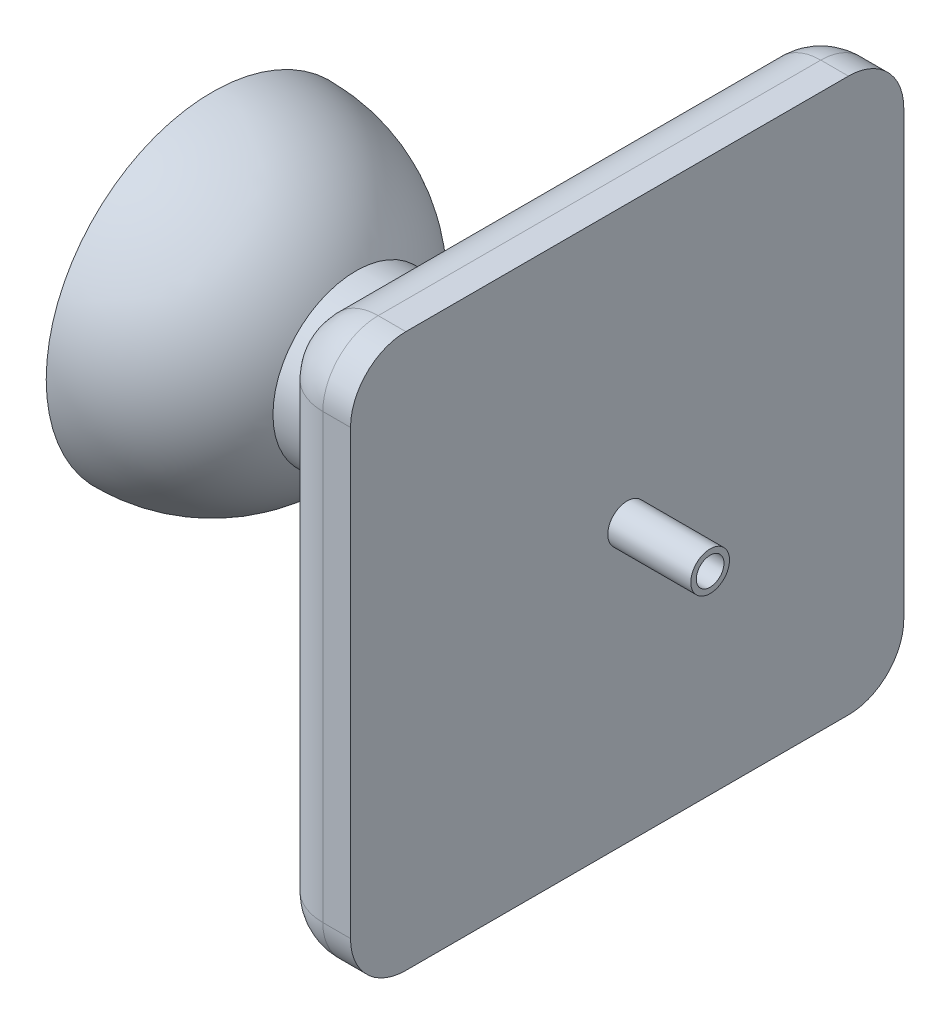
SolidWorks part; units mm, degrees
ref_plane "Alzado" through (0, 0, 0) normal (0, 0, 1) x (1, 0, 0)
ref_plane "Planta" through (0, 0, 0) normal (0, 1, 0) x (1, 0, 0)
ref_plane "Vista lateral" through (0, 0, 0) normal (1, 0, 0) x (0, 0, -1)
sketch "Croquis2" plane through (0, 0, 0) normal (0, 0, 1) x (1, 0, 0)
  line L2 (0, 0) -> (25, 0) construction
  arc A0 (25, 0) -> (0, 25) centre (0, 0) ccw
  dimension "D1" = 50
revolve "Revolución-Lámina1" add sketch "Croquis2" angle 360 about L2
sketch "Croquis3" plane through (0, 0, 0) normal (-1, 0, 0) x (0, 0, 1)
  circle A0 centre (0, 0) radius 15
  dimension "D1" = 30
extrude "Saliente-Extruir1" add sketch "Croquis3" against normal blind 20 and the other way up to surface from offset 40 offset against normal yes
sketch "Croquis4" plane through (60, 0, 0) normal (1, 0, 0) x (0, 0, -1)
  line L1 (-50, -50) -> (50, -50)
  line L2 (-50, -50) -> (-50, 50)
  line L3 (-50, 50) -> (50, 50)
  line L4 (50, -50) -> (50, 50)
  line L5 (-50, -50) -> (50, 50) construction
  line L6 (-50, 50) -> (50, -50) construction
  point P0 (0, 0)
  dimension "D1" = 100
  dimension "D2" = 100
extrude "Saliente-Extruir2" add sketch "Croquis4" along normal blind 15
fillet "Redondeo1" radius 10 4 edges at (67.5, -50, -50) (67.5, -50, 50) (67.5, 50, 50) (67.5, 50, -50)
fillet "Redondeo2" radius 10 8 edges at (60, -47.0711, -47.0711) (60, -50, 0) (60, -47.0711, 47.0711) (60, 0, 50) (60, 47.0711, 47.0711) (60, 50, 0) (60, 47.0711, -47.0711) (60, 0, -50)
sketch "Croquis5" plane through (75, 0, 0) normal (1, 0, 0) x (0, 0, -1)
  circle A0 centre (0, 0) radius 3.5
  circle A1 centre (0, 0) radius 2.5
  dimension "D1" = 7
  dimension "D2" = 5
extrude "Saliente-Extruir3" add sketch "Croquis5" along normal blind 15
